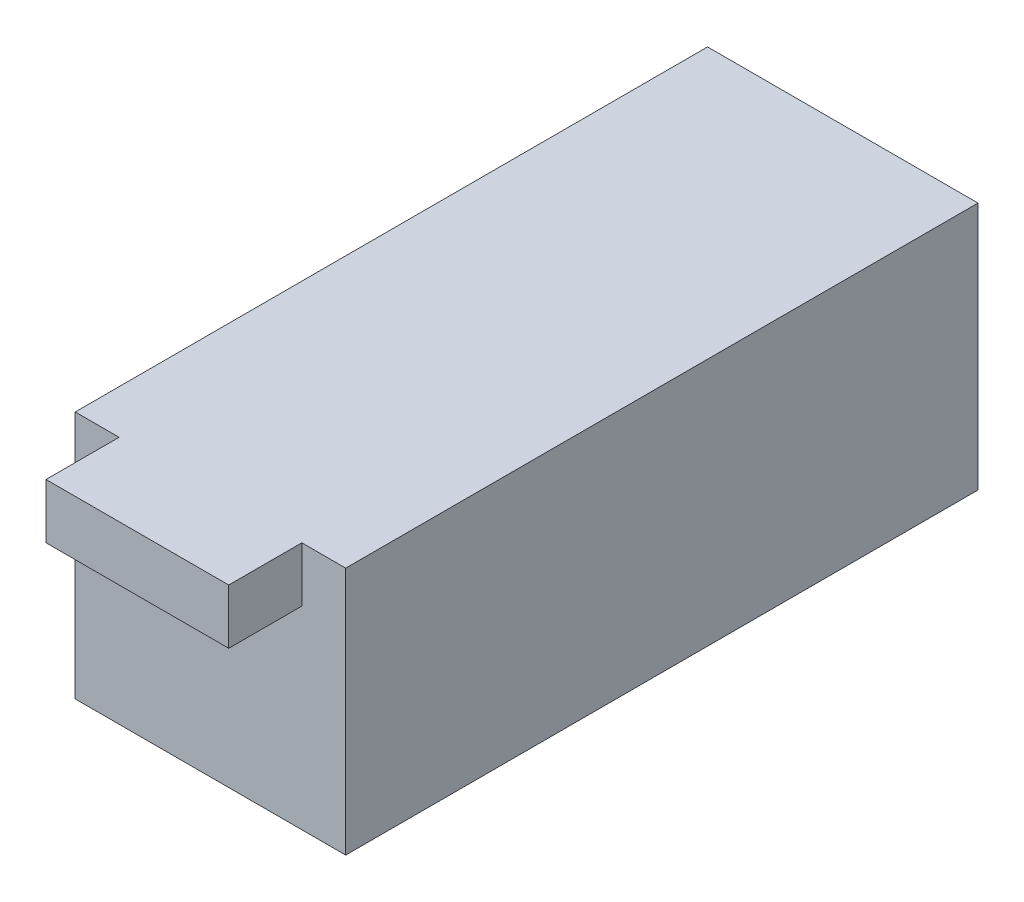
SolidWorks part; units mm, degrees
ref_plane "Front Plane" through (0, 0, 0) normal (0, 0, 1) x (1, 0, 0)
ref_plane "Top Plane" through (0, 0, 0) normal (0, 1, 0) x (1, 0, 0)
ref_plane "Right Plane" through (0, 0, 0) normal (1, 0, 0) x (0, 0, -1)
sketch "Sketch2" plane through (0, 0, 0) normal (0, 0, 1) x (1, 0, 0)
  line L1 (37, -34) -> (-37, -34)
  line L2 (37, -34) -> (37, 34)
  line L3 (37, 34) -> (-37, 34)
  line L4 (-37, -34) -> (-37, 34)
  line L5 (37, -34) -> (-37, 34) construction
  line L6 (37, 34) -> (-37, -34) construction
  point P0 (0, 0)
  dimension "D1" = 68
  dimension "D2" = 74
extrude "Boss-Extrude1" add sketch "Sketch2" along normal blind 173
sketch "Sketch3" plane through (0, 0, 173) normal (0, 0, 1) x (1, 0, 0)
  line L0 (37, 34) -> (-37, 34) construction
  line L1 (-25, 34) -> (25, 34)
  line L2 (-25, 34) -> (-25, 19)
  line L3 (-25, 19) -> (25, 19)
  line L4 (25, 34) -> (25, 19)
  line L5 (0, 0) -> (0, 19) construction
  dimension "D1" = 50
  dimension "D2" = 15
extrude "Boss-Extrude2" add sketch "Sketch3" along normal blind 20
